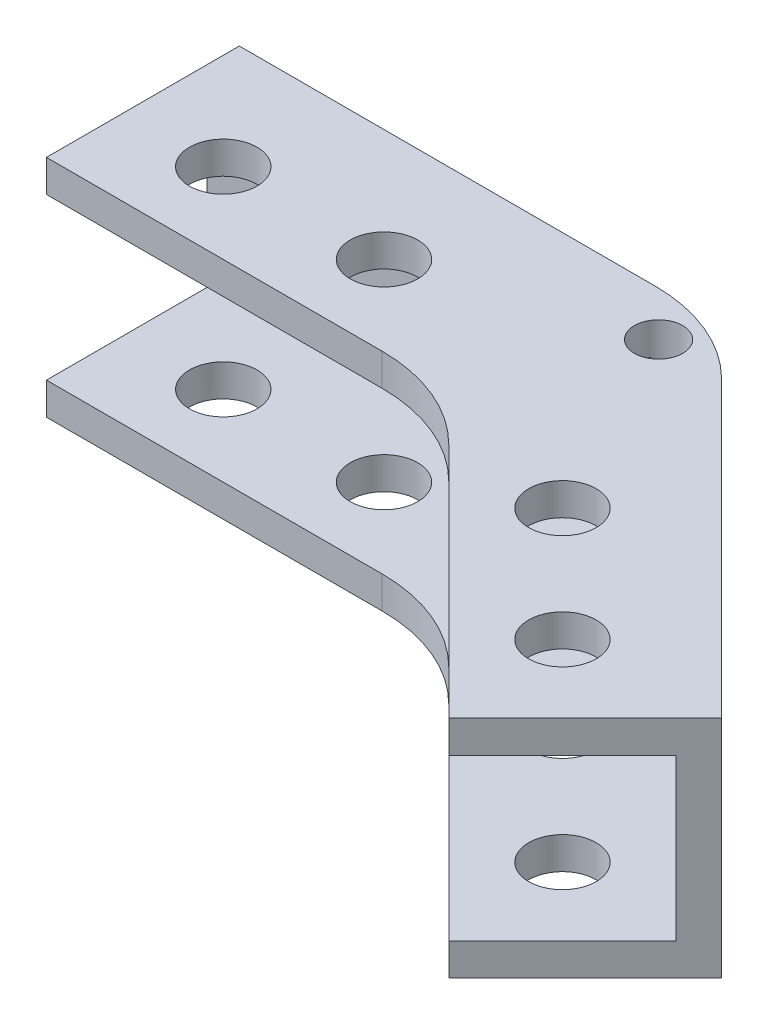
SolidWorks part; units mm, degrees
ref_plane "Front Plane" through (0, 0, 0) normal (0, 0, 1) x (1, 0, 0)
ref_plane "Top Plane" through (0, 0, 0) normal (0, 1, 0) x (1, 0, 0)
ref_plane "Right Plane" through (0, 0, 0) normal (1, 0, 0) x (0, 0, -1)
sketch "Sketch1" plane through (0, 0, 0) normal (0, 1, 0) x (1, 0, 0)
  line L0 (-27.1842, 10) -> (2.8158, 10)
  line L1 (2.8158, 10) -> (24.029, -11.2132)
  line L2 (24.029, -11.2132) -> (22.6148, -12.6274)
  line L3 (22.6148, -12.6274) -> (1.9874, 8)
  line L4 (1.9874, 8) -> (-27.1842, 8)
  line L5 (-27.1842, 8) -> (-27.1842, 10)
  dimension "D1" = 225
  dimension "D2" = 2
  dimension "D3" = 2
  dimension "D4" = 30
  dimension "D5" = 30
extrude "Boss-Extrude1" add sketch "Sketch1" along normal blind 14
sketch "Sketch2" plane through (0, 14, 0) normal (0, 1, 0) x (1, 0, 0)
  line L0 (-27.1842, 8) -> (-27.1842, -2)
  line L1 (-27.1842, -2) -> (-2.1547, -2)
  line L2 (-2.1547, -2) -> (15.5437, -19.6985)
  line L3 (15.5437, -19.6985) -> (22.6148, -12.6274)
  line L4 (22.6148, -12.6274) -> (1.9874, 8)
  line L5 (1.9874, 8) -> (-27.1842, 8)
  dimension "D1" = 10
  dimension "D2" = 10
extrude "Boss-Extrude2" add sketch "Sketch2" against normal blind 2
sketch "Sketch3" plane through (0, 0, 0) normal (0, -1, 0) x (1, 0, 0)
  line L0 (-27.1842, -8) -> (-27.1842, 2)
  line L1 (-27.1842, 2) -> (-2.1547, 2)
  line L2 (-2.1547, 2) -> (15.5437, 19.6985)
  line L3 (15.5437, 19.6985) -> (22.6148, 12.6274)
  line L4 (22.6148, 12.6274) -> (1.9874, -8)
  line L5 (1.9874, -8) -> (-27.1842, -8)
extrude "Boss-Extrude3" add sketch "Sketch3" against normal blind 2
sketch "Sketch4" plane through (0, 14, 0) normal (0, 1, 0) x (1, 0, 0)
  line L0 (2.8158, 10) -> (-27.1842, 10) construction
  line L1 (-27.1842, 10) -> (-27.1842, -2) construction
  line L2 (24.029, -11.2132) -> (2.8158, 10) construction
  line L3 (15.5437, -19.6985) -> (24.029, -11.2132) construction
  circle A0 centre (-21.1842, 3) radius 2.1
  circle A1 centre (-11.1842, 3) radius 2.1
  circle A2 centre (7.7656, -4.8492) radius 2.1
  circle A3 centre (14.8366, -11.9203) radius 2.1
  dimension "D1" = 4.2
  dimension "D2" = 4.2
  dimension "D3" = 4.2
  dimension "D4" = 4.2
  dimension "D5" = 7
  dimension "D6" = 7
  dimension "D7" = 6
  dimension "D8" = 16
  dimension "D9" = 7
  dimension "D10" = 7
  dimension "D11" = 6
  dimension "D12" = 16
extrude "Cut-Extrude1" cut sketch "Sketch4" against normal blind 15
sketch "Sketch5" plane through (0, 14, 0) normal (0, 1, 0) x (1, 0, 0)
  line L0 (2.8158, 10) -> (-2.1547, -2) construction
  circle A0 centre (1.6678, 7.2284) radius 1.5
  dimension "D2" = 3
  dimension "D1" = 3
extrude "Cut-Extrude2" cut sketch "Sketch5" against normal blind 15
sketch "Sketch6" plane through (0, 0, -10) normal (0, 0, -1) x (-1, 0, 0)
  line L0 (-2.8158, 14) -> (-2.8158, 0) construction
  line L1 (-2.8158, 10) -> (4.1842, 10)
  line L2 (-2.8158, 10) -> (-2.8158, 4)
  line L3 (-2.8158, 4) -> (4.1842, 4)
  line L4 (4.1842, 10) -> (4.1842, 4)
  line L5 (-2.8158, 14) -> (27.1842, 14) construction
  dimension "D1" = 6
  dimension "D2" = 0
  dimension "D3" = 7
  dimension "D4" = 4
extrude "Cut-Extrude3" cut sketch "Sketch6" against normal blind 15
sketch "Sketch7" plane through (6.4079, 0, -6.4079) normal (0.7071, 0, -0.7071) x (-0.7071, 0, -0.7071)
  line L0 (-24.92, 0) -> (5.08, 0) construction
  line L1 (5.08, 10) -> (-1.92, 10)
  line L2 (5.08, 10) -> (5.08, 4)
  line L3 (5.08, 4) -> (-1.92, 4)
  line L4 (-1.92, 10) -> (-1.92, 4)
  dimension "D1" = 7
  dimension "D2" = 4
extrude "Cut-Extrude4" cut sketch "Sketch7" against normal blind 15
fillet "Fillet2" radius 10 2 edges at (2.8158, 2, -10) (2.8158, 12, -10)
fillet "Fillet3" radius 10 2 edges at (-2.1547, 1, 2) (-2.1547, 13, 2)
